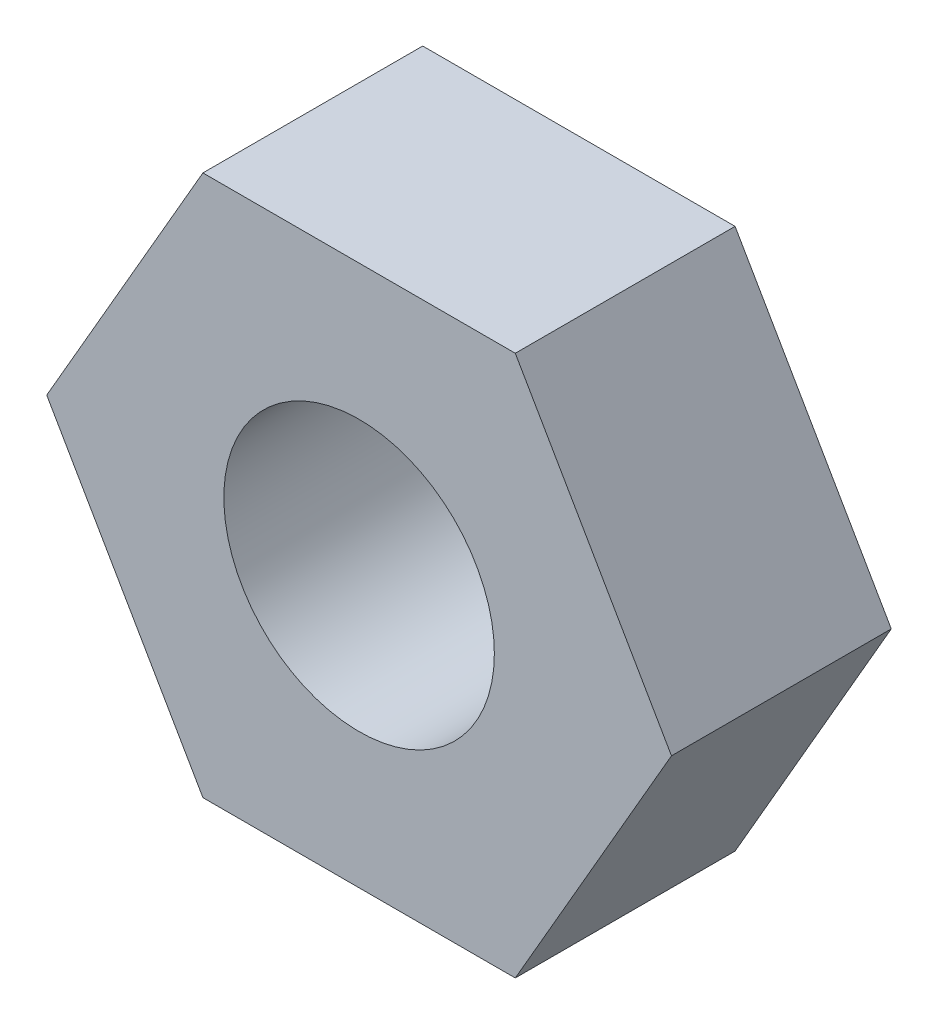
SolidWorks part; units mm, degrees
ref_plane "Front Plane" through (0, 0, 0) normal (0, 0, 1) x (1, 0, 0)
ref_plane "Top Plane" through (0, 0, 0) normal (0, 1, 0) x (1, 0, 0)
ref_plane "Right Plane" through (0, 0, 0) normal (1, 0, 0) x (0, 0, -1)
sketch "Sketch1" plane through (0, 0, 0) normal (0, 0, 1) x (1, 0, 0)
  line L0 (1.8475, 0) -> (0.9238, 1.6)
  line L1 (0.9238, 1.6) -> (-0.9238, 1.6)
  line L2 (-0.9238, 1.6) -> (-1.8475, 0)
  line L3 (-1.8475, 0) -> (-0.9238, -1.6)
  line L4 (-0.9238, -1.6) -> (0.9238, -1.6)
  line L5 (0.9238, -1.6) -> (1.8475, 0)
  circle A0 centre (0, 0) radius 0.8
extrude "Nut" add sketch "Sketch1" along normal blind 1.3
